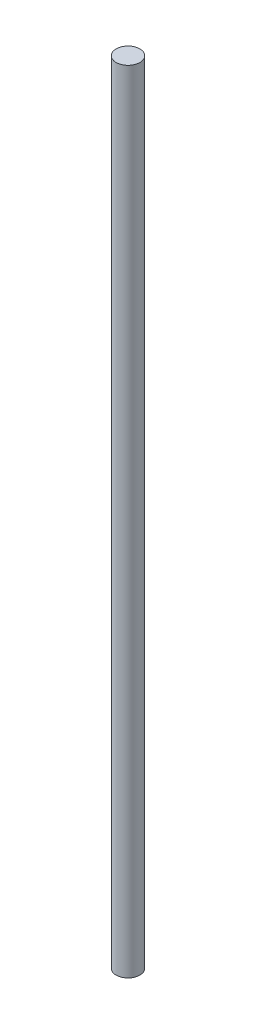
SolidWorks part; units mm, degrees
ref_plane "Front Plane" through (0, 0, 0) normal (0, 0, 1) x (1, 0, 0)
ref_plane "Top Plane" through (0, 0, 0) normal (0, 1, 0) x (1, 0, 0)
ref_plane "Right Plane" through (0, 0, 0) normal (1, 0, 0) x (0, 0, -1)
sketch "Sketch1" plane through (0, 0, 0) normal (0, 1, 0) x (1, 0, 0)
  circle A0 centre (0, 0) radius 1.5
  dimension "D1" = 3
extrude "Boss-Extrude1" add sketch "Sketch1" along normal blind 100.076
